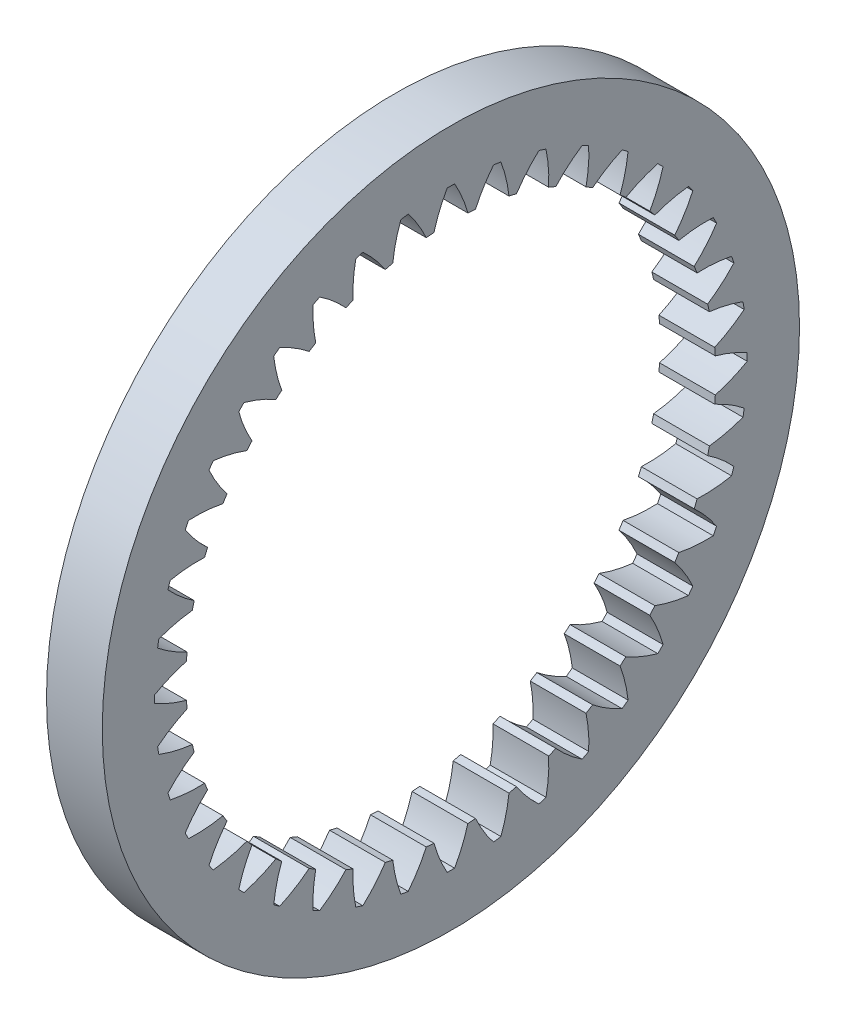
SolidWorks part; units mm, degrees
ref_plane "Plane1" through (0, 0, 0) normal (0, 0, 1) x (1, 0, 0)
ref_plane "Plane2" through (0, 0, 0) normal (0, 1, 0) x (1, 0, 0)
ref_plane "Plane3" through (0, 0, 0) normal (1, 0, 0) x (0, 0, -1)
sketch "HoldingSke" plane through (0, 0, 0) normal (0, 1, 0) x (1, 0, 0)
  line L0 (0, 0) -> (0.5107, -0.4285)
  line L1 (-15, 0) -> (100, 0) construction
  line L2 (0, 0) -> (-2.1039, 2.3779)
  line L3 (0, 0) -> (-11.863, 4.5341)
  line L4 (0, 0) -> (6.6156, 5.5511)
  line L5 (0, 0) -> (-23.7986, -8.8762)
  line L6 (0, 0) -> (-10.5278, -7.1032)
  line L7 (-2.1039, 2.3779) -> (3.3635, 27.1825)
  line L8 (-76.2, 3.8779) -> (-54.61, 3.8779)
  line L9 (-71.009, 38.7566) -> (-53.1078, 45.2721)
  line L10 (-76.2, 71.12) -> (104.1128, 71.12)
  line L11 (0, 0) -> (-6, 0)
  line L12 (-76.2, 101.6) -> (-76.147, 101.6)
  line L13 (24.9733, 27.94) -> (52.9518, 28.4284)
  line L14 (24.9733, 27.94) -> (24.9743, 27.94)
  line L15 (24.9733, 27.94) -> (100.4006, 29.5858)
  circle A0 centre (0, 0) radius 37.5
  circle A1 centre (0, 0) radius 12.7
  circle A2 centre (0, 0) radius 12.7
  dimension "MHD" = 25.4
  dimension "Hub_dia" = 25.4
  dimension "Diameter" = 75
  dimension "Num_teeth" = 40
  dimension "Pitch" = 0.6667
  dimension "Overall_len" = 25.4
  dimension "Show_teeth" = 40
  dimension "Thickness" = 12.7
  dimension "OAL" = 25.4001
  dimension "T_dim" = 21.59
  dimension "Ap" = 20
  dimension "H" = 19.05
  dimension "Pitch_radius" = 180.3128
  dimension "Width" = 6
  dimension "Backlash" = 0.053
  dimension "Addendum_fac" = 1
  dimension "Dedendum_fac" = 1.25
  dimension "Clearance_fac" = 0.25
  dimension "Dedendum_add" = 0.001
  dimension "Module" = 1.5
sketch "BasProSke" plane through (0, 0, 0) normal (0, 1, 0) x (1, 0, 0)
  line L0 (-10, 0) -> (60, 0) construction
  line L1 (0, 28.5) -> (0, 37.5)
  line L2 (0, 28.5) -> (6, 28.5)
  line L3 (6, 28.5) -> (6, 37.5)
  line L4 (6, 37.5) -> (0, 37.5)
  dimension "Diameter" = 75
  dimension "Thickness" = 6
  dimension "Inside_diameter" = 57
revolve "Base-Revolve" add sketch "BasProSke" angle 360 about L0
sketch "TooCutSke" plane through (0, 0, 0) normal (1, 0, 0) x (0, 0, -1)
  line L3 (1.3103, 29.9714) -> (1.3103, 53.6633) construction
  line L4 (0, 0) -> (0, 59.563) construction
  line L5 (0, 0) -> (-5.3609, 68.1169) construction
  line L6 (-12.6387, 24.4555) -> (35.7355, 28.2626) construction
  circle A0 centre (0, 0) radius 30 construction
  circle A1 centre (0, 0) radius 31.876 construction
  circle A2 centre (0, 0) radius 25.3717 construction
  circle A3 centre (0, 0) radius 28.4746 construction
  arc A4 (1.829, 28.4158) -> (0.3986, 31.8735) centre (-12.6387, 24.4555) ccw
  arc A5 (1.829, 28.4158) -> (-1.829, 28.4158) centre (0, 0) ccw
  arc A6 (0.3986, 31.8735) -> (-0.3986, 31.8735) centre (0, 0) ccw
  arc A7 (-0.3986, 31.8735) -> (-1.829, 28.4158) centre (12.6387, 24.4555) ccw
  dimension "Pitch_dia" = 60
  dimension "Base_dia" = 50.7434
  dimension "Root_dia" = 63.752
  dimension "Overcut_dia" = 56.9492
  dimension "Flank_rad" = 15
  dimension "Half_ang" = 4.5
  dimension "Half_CT" = 1.3103
extrude "ToothCut" cut sketch "TooCutSke" along normal through all
fillet "Breaks" [suppressed] radius 0.15
fillet "RootFillets" [suppressed] radius 0.376
pattern_circular "TeethCuts" count 40 every 9 about axis through (-10, 0, 0) along (1, 0, 0) of "RootFillets", "Breaks", "ToothCut"
equation "' \"Module@HoldingSke\" = 6.35"
equation "' \"Num_teeth@HoldingSke\" = 24"
equation "' \"Ap@HoldingSke\" =  14.5"
equation "' \"Ap@HoldingSke\" = 14.5"
equation "' \"Width@HoldingSke\" = 12"
equation "' \"Diameter@HoldingSke\" = 8 * 25.4"
equation "' \"Show_teeth@HoldingSke\" = 100"
equation "' \"Backlash@HoldingSke\" = 0.009 * 25.4"
equation "' \"Addendum_fac@HoldingSke\" = 1.0"
equation "' \"Dedendum_fac@HoldingSke\" = 1.25"
equation "' \"Dedendum_add@HoldingSke\" = 0.00005 * 25.4"
equation "' \"Clearance_fac@HoldingSke\" = 0.25"
equation "\"Pitch@HoldingSke\" = 1 / \"Module@HoldingSke\" "
equation "\"Overcut_dia@TooCutSke\" = (\"Num_teeth@HoldingSke\" - 2 * \"Addendum_fac@HoldingSke\") / \"Pitch@HoldingSke\" - 0.002 * 25.4"
equation "\"Pitch_dia@TooCutSke\" = \"Num_teeth@HoldingSke\" / \"Pitch@HoldingSke\""
equation "\"Base_dia@TooCutSke\" = \"Num_teeth@HoldingSke\" / \"Pitch@HoldingSke\" * cos((\"Ap@HoldingSke\"  * 3.14159265 / 180)) * 0.90"
equation "\"Root_dia@TooCutSke\" = \"Num_teeth@HoldingSke\"  / \"Pitch@HoldingSke\" + 2 *  \"Dedendum_fac@HoldingSke\"/ \"Pitch@HoldingSke\" + \"Dedendum_add@HoldingSke\" * 2"
equation "\"Half_ang@TooCutSke\" = 180 / \"Num_teeth@HoldingSke\""
equation "\"Half_CT@TooCutSke\" = \"Num_teeth@HoldingSke\" / \"Pitch@HoldingSke\" * sin((3.14159265 / 2 / \"Num_teeth@HoldingSke\")) / 2 + 10 * \"Backlash@HoldingSke\" / 4"
equation "\"Flank_rad@TooCutSke\" = \"Num_teeth@HoldingSke\" / \"Pitch@HoldingSke\" / 4"
equation "\"Radius@RootFillets\"= \"Clearance_fac@HoldingSke\" / \"Pitch@HoldingSke\" + \"Dedendum_add@HoldingSke\""
equation "\"Break_rad@Breaks\" = 0.02 / \"Pitch@HoldingSke\" * 5"
equation "\"Num_teeth@TeethCuts\" = int( \"Show_teeth@HoldingSke\" ) + 1"
equation "\"Num_teeth@TeethCuts\" = ((sgn( \"Num_teeth@TeethCuts\" - \"Num_teeth@HoldingSke\" )-1)*( \"Num_teeth@TeethCuts\" - \"Num_teeth@HoldingSke\" ))/-2+ \"Num_teeth@HoldingSke\""
equation "\"Num_teeth@TeethCuts\" = ((sgn( \"Num_teeth@TeethCuts\" - 2.0)+1)*( \"Num_teeth@TeethCuts\" - 2.0))/2 +2.0"
equation "\"Angle@TeethCuts\" = 360.0 / \"Num_teeth@HoldingSke\""
equation "\"Diameter@BasProSke\" = \"Num_teeth@HoldingSke\"  / \"Pitch@HoldingSke\" + 2 *  \"Dedendum_fac@HoldingSke\"/ \"Pitch@HoldingSke\" + \"Dedendum_add@HoldingSke\" * 2 + 0.002 * 25.4"
equation "\"Diameter@BasProSke\" = ((sgn( \"Diameter@BasProSke\"  - \"Diameter@HoldingSke\" )+1)*( \"Diameter@BasProSke\"  - \"Diameter@HoldingSke\" ))/2 + \"Diameter@HoldingSke\""
equation "\"Inside_diameter@BasProSke\" =  (\"Num_teeth@HoldingSke\" - 2 * \"Addendum_fac@HoldingSke\") / \"Pitch@HoldingSke\" "
equation "\"Thickness@BasProSke\"  = \"Width@HoldingSke\""
